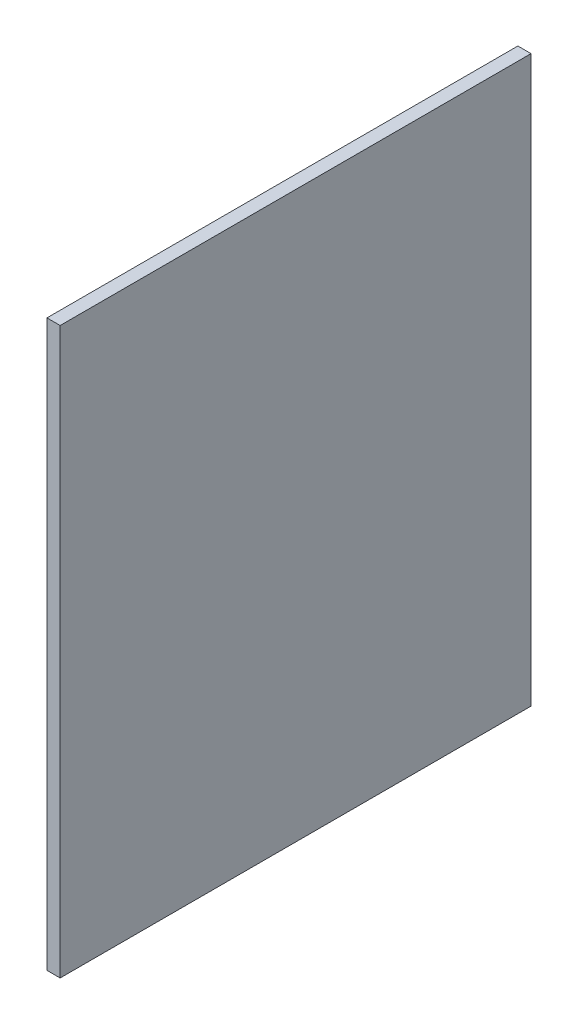
SolidWorks part; units mm, degrees
ref_plane "Front Plane" through (0, 0, 0) normal (0, 0, 1) x (1, 0, 0)
ref_plane "Top Plane" through (0, 0, 0) normal (0, 1, 0) x (1, 0, 0)
ref_plane "Right Plane" through (0, 0, 0) normal (1, 0, 0) x (0, 0, -1)
sketch "Sketch1" plane through (0, 0, 0) normal (0, 0, 1) x (1, 0, 0)
  line L0 (0, 1500) -> (0, -1500)
  line L1 (35, -1500) -> (-35, -1500)
  line L2 (35, -1500) -> (35, 1500)
  line L4 (35, 1500) -> (-35, 1500)
  line L5 (-35, -1500) -> (-35, 1500)
  line L6 (35, 0) -> (-35, 0)
  point P12 (0, 0)
  dimension "D1" = 70
  dimension "D2" = 1500
  dimension "D3" = 1500
extrude "Boss-Extrude1" add sketch "Sketch1" along normal blind 2500 contours L5 L4 L2 L1
